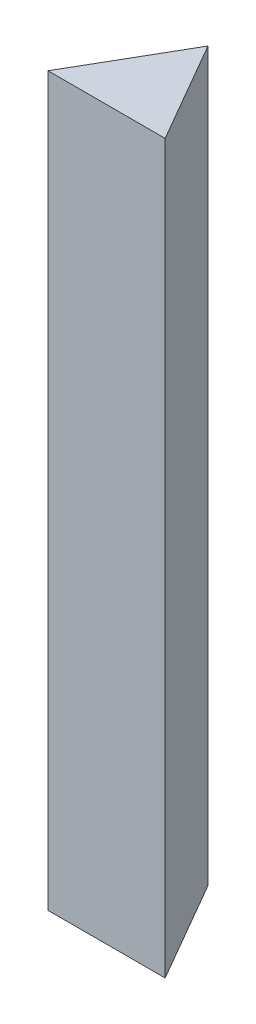
SolidWorks part; units mm, degrees
ref_plane "Front Plane" through (0, 0, 0) normal (0, 0, 1) x (1, 0, 0)
ref_plane "Top Plane" through (0, 0, 0) normal (0, 1, 0) x (1, 0, 0)
ref_plane "Right Plane" through (0, 0, 0) normal (1, 0, 0) x (0, 0, -1)
sketch "Sketch1" plane through (0, 0, 0) normal (0, 1, 0) x (1, 0, 0)
  line L1 (-2.4, 0) -> (0, 4.1569)
  line L2 (0, 4.1569) -> (2.4, 0)
  line L3 (2.4, 0) -> (-2.4, 0)
  point P0 (0, 0)
  dimension "D1" = 4.8
extrude "Boss-Extrude1" add sketch "Sketch1" along normal blind 29.8
